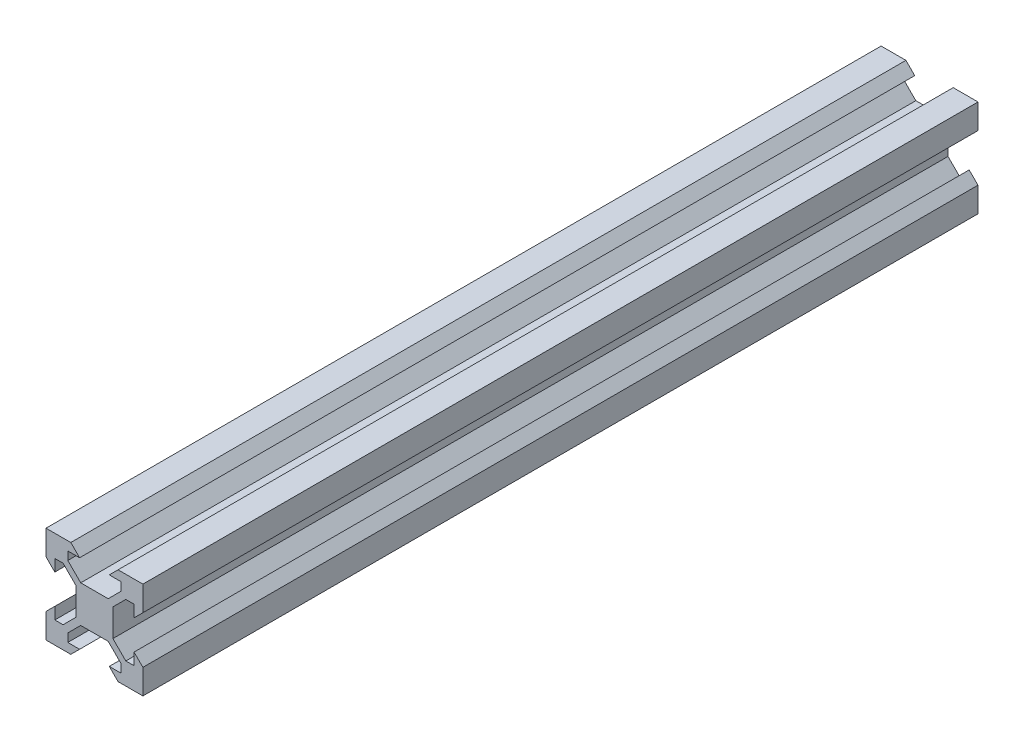
SolidWorks part; units mm, degrees
ref_plane "Front Plane" through (0, 0, 0) normal (0, 0, 1) x (1, 0, 0)
ref_plane "Top Plane" through (0, 0, 0) normal (0, 1, 0) x (1, 0, 0)
ref_plane "Right Plane" through (0, 0, 0) normal (1, 0, 0) x (0, 0, -1)
sketch "Sketch1" plane through (0, 0, 0) normal (0, 0, 1) x (1, 0, 0)
  line L1 (0, 0) -> (20, 0)
  line L2 (0, 0) -> (0, 20)
  line L3 (0, 20) -> (20, 20)
  line L4 (20, 0) -> (20, 20)
  line L5 (0, 0) -> (20, 20) construction
  line L6 (0, 20) -> (20, 0) construction
  point P4 (10, 10)
  dimension "D1" = 20
  dimension "D2" = 20
extrude "Boss-Extrude1" add sketch "Sketch1" along normal blind 172.4
sketch "Sketch2" plane through (0, 0, 172.4) normal (0, 0, 1) x (1, 0, 0)
  line L4 (0, 0) -> (20, 20) construction
  line L5 (4.5, 18.18) -> (6.94, 18.18)
  line L6 (4.5, 16.4758) -> (4.5, 18.18)
  line L15 (7.1658, 13.81) -> (4.5, 16.4758)
  line L17 (12.8342, 13.81) -> (7.1658, 13.81)
  line L27 (15.5, 16.4758) -> (12.8342, 13.81)
  line L29 (15.5, 18.18) -> (15.5, 16.4758)
  line L31 (13.06, 18.18) -> (15.5, 18.18)
  line L33 (14.88, 20) -> (5.12, 20)
  line L35 (6.94, 18.18) -> (5.12, 20)
  line L54 (14.88, 20) -> (13.06, 18.18)
  line L56 (14.88, 0) -> (13.06, 1.82)
  line L57 (6.94, 1.82) -> (5.12, 0)
  line L58 (14.88, 0) -> (5.12, 0)
  line L68 (13.06, 1.82) -> (15.5, 1.82)
  line L71 (15.5, 1.82) -> (15.5, 3.5242)
  line L81 (15.5, 3.5242) -> (12.8342, 6.19)
  line L82 (12.8342, 6.19) -> (7.1658, 6.19)
  line L83 (7.1658, 6.19) -> (4.5, 3.5242)
  line L84 (4.5, 3.5242) -> (4.5, 1.82)
  line L85 (4.5, 1.82) -> (6.94, 1.82)
  line L136 (20, 0) -> (10, 0) construction
  line L137 (0, 0) -> (20, 0) construction
  line L186 (1.82, 4.5) -> (1.82, 6.94)
  line L187 (3.5242, 4.5) -> (1.82, 4.5)
  line L188 (6.19, 7.1658) -> (3.5242, 4.5)
  line L189 (6.19, 12.8342) -> (6.19, 7.1658)
  line L190 (3.5242, 15.5) -> (6.19, 12.8342)
  line L191 (1.82, 15.5) -> (3.5242, 15.5)
  line L192 (1.82, 13.06) -> (1.82, 15.5)
  line L193 (0, 14.88) -> (0, 5.12)
  line L194 (1.82, 6.94) -> (0, 5.12)
  line L195 (0, 14.88) -> (1.82, 13.06)
  line L203 (20, 14.88) -> (18.18, 13.06)
  line L205 (18.18, 6.94) -> (20, 5.12)
  line L206 (20, 14.88) -> (20, 5.12)
  line L207 (18.18, 13.06) -> (18.18, 15.5)
  line L208 (18.18, 15.5) -> (16.4758, 15.5)
  line L209 (16.4758, 15.5) -> (13.81, 12.8342)
  line L210 (13.81, 12.8342) -> (13.81, 7.1658)
  line L211 (13.81, 7.1658) -> (16.4758, 4.5)
  line L212 (16.4758, 4.5) -> (18.18, 4.5)
  line L213 (18.18, 4.5) -> (18.18, 6.94)
extrude "Cut-Extrude1" cut sketch "Sketch2" against normal through all
